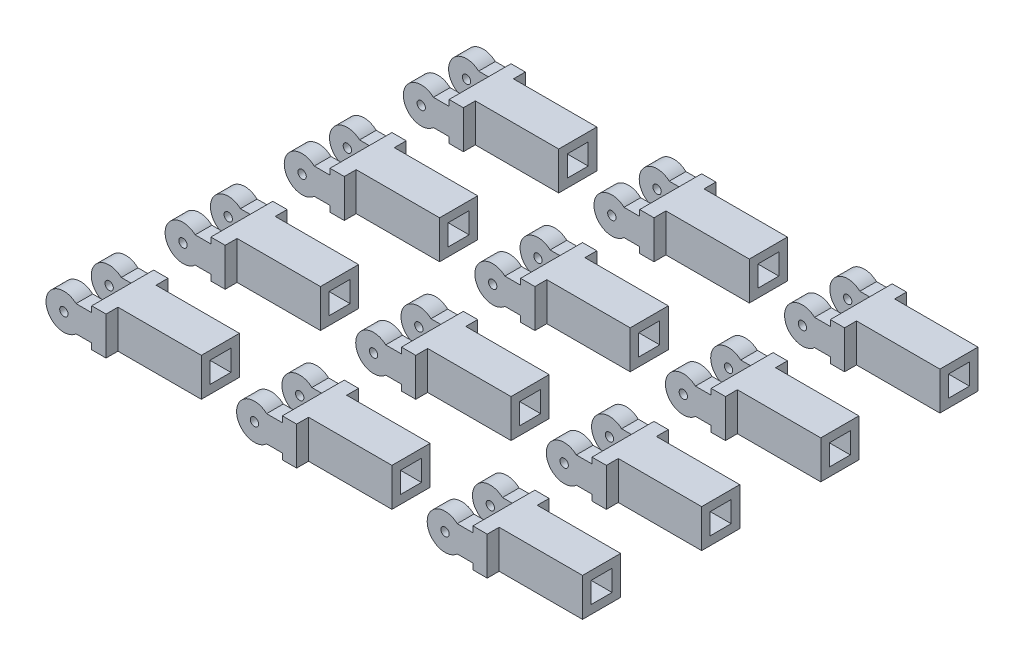
SolidWorks part; units mm, degrees
ref_plane "前视基准面" through (0, 0, 0) normal (0, 0, 1) x (1, 0, 0)
ref_plane "上视基准面" through (0, 0, 0) normal (0, 1, 0) x (1, 0, 0)
ref_plane "右视基准面" through (0, 0, 0) normal (1, 0, 0) x (0, 0, -1)
sketch "草图1" plane through (0, 0, 0) normal (1, 0, 0) x (0, 0, -1)
  line L1 (-1.6, -1.6) -> (1.6, -1.6)
  line L2 (-1.6, -1.6) -> (-1.6, 1.6)
  line L3 (-1.6, 1.6) -> (1.6, 1.6)
  line L4 (1.6, -1.6) -> (1.6, 1.6)
  line L5 (-1.6, -1.6) -> (1.6, 1.6) construction
  line L6 (-1.6, 1.6) -> (1.6, -1.6) construction
  line L7 (-0.88, -0.88) -> (0.88, -0.88)
  line L8 (-0.88, -0.88) -> (-0.88, 0.88)
  line L9 (-0.88, 0.88) -> (0.88, 0.88)
  line L10 (0.88, -0.88) -> (0.88, 0.88)
  line L11 (-0.88, -0.88) -> (0.88, 0.88) construction
  line L12 (-0.88, 0.88) -> (0.88, -0.88) construction
  point P0 (0, 0)
  point P6 (0, 0)
  dimension "D1" = 3.2
  dimension "D2" = 1.76
extrude "凸台-拉伸1" add sketch "草图1" along normal blind 7
sketch "草图2" plane through (0, 0, 0) normal (-1, 0, 0) x (0, 0, 1)
  line L4 (-1.6, 1.6) -> (-1.6, -1.6)
  line L5 (-1.6, -1.6) -> (1.6, -1.6)
  line L6 (1.6, -1.6) -> (1.6, 1.6)
  line L7 (1.6, 1.6) -> (-1.6, 1.6)
  line L8 (-1.6, 1.6) -> (-1.6, -1.6)
  line L9 (-1.6, -1.6) -> (1.6, -1.6)
  line L10 (1.6, -1.6) -> (1.6, 1.6)
  line L11 (1.6, 1.6) -> (-1.6, 1.6)
  dimension "D1" = 0
extrude "凸台-拉伸2" add sketch "草图2" along normal blind 1.2
sketch "草图3" plane through (0, 0, 0) normal (0, 0, 1) x (1, 0, 0)
  line L0 (-1.2, 0) -> (-3.5398, 0) construction
  line L1 (-1.2, 1.6) -> (-1.2, -1.6) construction
  line L2 (-1.2, 1.1) -> (-2.52, 1.1)
  line L3 (-1.2, 1.1) -> (-1.2, -1.1)
  line L4 (-1.2, -1.1) -> (-2.52, -1.1)
  line L5 (-2.52, 1.1) -> (-2.52, -1.1)
  line L6 (0, 0) -> (-1.2, 0) construction
  circle A0 centre (-3.5398, 0) radius 1.5
  dimension "D3" = 3
  dimension "D1" = 2.2
  dimension "D2" = 1.32
extrude "凸台-拉伸3" add sketch "草图3" against normal mid plane 5.2 contours A0 L4 L3 L2 | L5 A0 | L5 A0
sketch "草图4" plane through (0, 0, 0) normal (0, 0, 1) x (1, 0, 0)
  line L4 (-1.2, 1.1) -> (-2.52, 1.1)
  line L5 (-2.52, 1.1) -> (-2.52, -1.1)
  line L6 (-2.52, -1.1) -> (-1.2, -1.1)
  line L7 (-1.2, -1.1) -> (-1.2, 1.1)
  line L8 (-1.2, 1.1) -> (-2.52, 1.1)
  line L10 (-2.52, -1.1) -> (-1.2, -1.1)
  line L11 (-1.2, -1.1) -> (-1.2, 1.1)
  circle A1 centre (-3.5398, 0) radius 1.5
  arc A2 (-2.52, 1.1) -> (-2.52, -1.1) centre (-3.5398, 0) ccw
  dimension "D1" = 0
  dimension "D2" = 0
extrude "切除-拉伸1" cut sketch "草图4" against normal mid plane 2.4
sketch "草图5" plane through (-1.2, 0, 0) normal (1, 0, 0) x (0, 0, -1)
  line L0 (-1.6, 1.6) -> (1.6, 1.6) construction
  line L1 (-2.6, -1.6) -> (2.6, -1.6)
  line L2 (-2.6, -1.6) -> (-2.6, 1.6)
  line L3 (-2.6, 1.6) -> (2.6, 1.6)
  line L4 (2.6, -1.6) -> (2.6, 1.6)
  line L5 (-2.6, -1.6) -> (2.6, 1.6) construction
  line L6 (-2.6, 1.6) -> (2.6, -1.6) construction
  line L7 (2.6, 1.1) -> (2.6, -1.1) construction
  point P0 (0, 0)
extrude "凸台-拉伸4" add sketch "草图5" along normal blind 1.2
sketch "草图6" plane through (0, 0, 1.2) normal (0, 0, -1) x (-1, 0, 0)
  circle A0 centre (3.5398, 0) radius 0.35
  dimension "D1" = 0.7
extrude "切除-拉伸2" cut sketch "草图6" against normal through all both and the other way through all
pattern_linear "阵列(线性)1" count 4 spacing 10 along (0, 0, 1) count 3 spacing 16 along (1, 0, 0) of bodies 111
